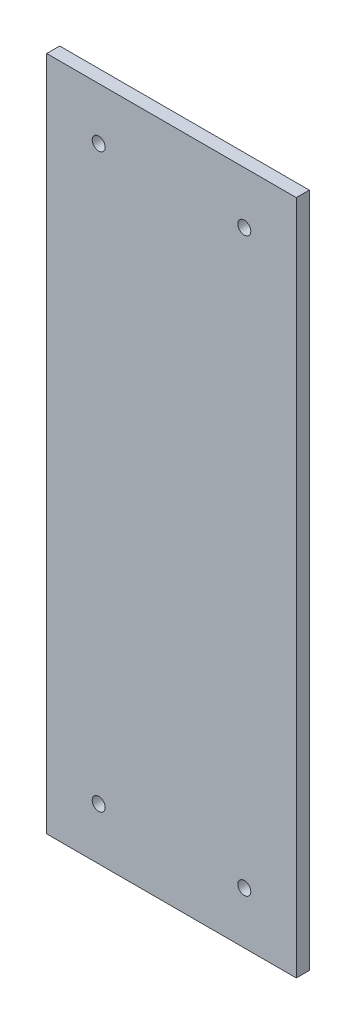
SolidWorks part; units mm, degrees
material "6061 Alloy"
ref_plane "Front" through (0, 0, 0) normal (0, 0, 1) x (1, 0, 0)
ref_plane "Top" through (0, 0, 0) normal (0, 1, 0) x (1, 0, 0)
ref_plane "Right" through (0, 0, 0) normal (1, 0, 0) x (0, 0, -1)
sketch "Sketch1" plane through (0, 0, 0) normal (0, 0, 1) x (1, 0, 0)
  line L1 (0, 0) -> (121.92, 0)
  line L2 (0, 0) -> (0, 330.2)
  line L3 (0, 330.2) -> (121.92, 330.2)
  line L4 (121.92, 0) -> (121.92, 330.2)
  dimension "D1" = 330.2
  dimension "D2" = 121.92
extrude "Boss-Extrude1" add sketch "Sketch1" along normal blind 6.35
sketch "Sketch2" plane through (0, 0, 6.35) normal (0, 0, 1) x (1, 0, 0)
  line L0 (0, 330.2) -> (0, 0) construction
  line L1 (121.92, 330.2) -> (0, 330.2) construction
  circle A0 centre (25.4, 304.8) radius 3.175
  dimension "D3" = 6.35
  dimension "D1" = 25.4
  dimension "D2" = 25.4
extrude "Cut-Extrude1" cut sketch "Sketch2" against normal blind 6.35
pattern_linear "LPattern1" count 2 spacing 71.12 along (1, 0, 0) count 2 spacing 279.4 along (0, -1, 0) of "Cut-Extrude1"
